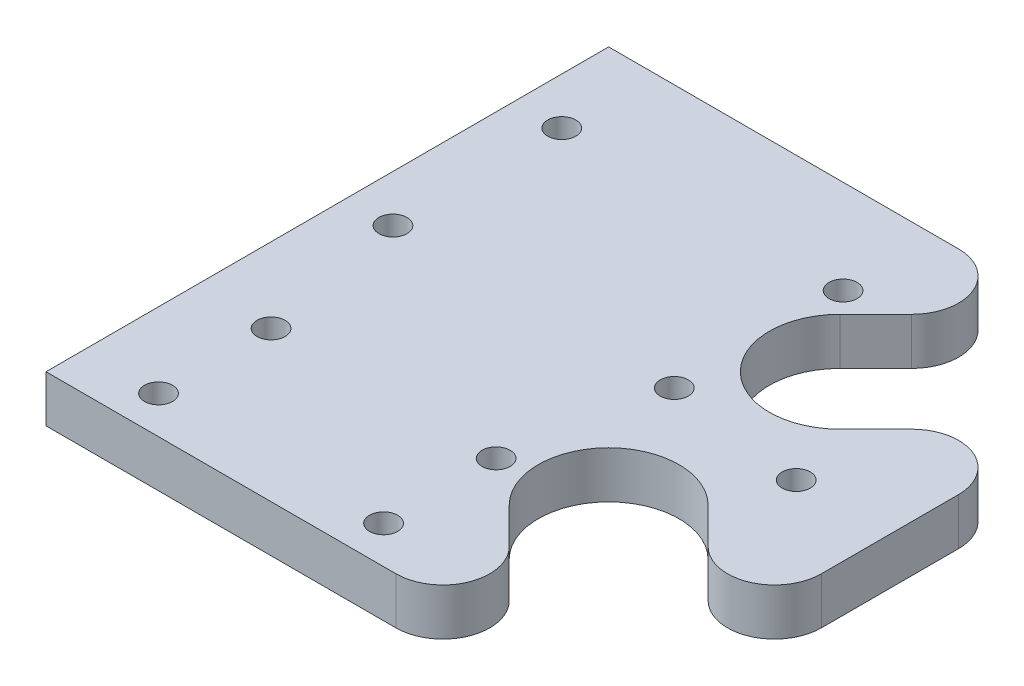
SolidWorks part; units mm, degrees
material "Thornel Mat VMA"
ref_plane "前视基准面" through (0, 0, 0) normal (0, 0, 1) x (1, 0, 0)
ref_plane "上视基准面" through (0, 0, 0) normal (0, 1, 0) x (1, 0, 0)
ref_plane "右视基准面" through (0, 0, 0) normal (1, 0, 0) x (0, 0, -1)
sketch "草图1" plane through (0, 0, 0) normal (0, 1, 0) x (1, 0, 0)
  line L1 (-30, -30) -> (30, -30)
  line L2 (-30, -30) -> (-30, 30)
  line L3 (-30, 30) -> (30, 30)
  line L4 (30, -30) -> (30, 30)
  line L5 (-30, -30) -> (30, 30) construction
  line L6 (-30, 30) -> (30, -30) construction
  point P0 (0, 0)
  dimension "D1" = 60
  dimension "D2" = 60
extrude "凸台-拉伸1" add sketch "草图1" along normal blind 5
sketch "草图2" plane through (0, 5, 0) normal (0, 1, 0) x (1, 0, 0)
  line L0 (-30, 0) -> (30, 0) construction
  line L1 (-30, 30) -> (-30, -30) construction
  line L2 (30, -30) -> (30, 30) construction
  line L3 (30, 30) -> (0, 0) construction
  line L4 (19.3934, 30) -> (7.019, 17.6256)
  line L5 (30, 30) -> (-30, 30) construction
  line L6 (30, 19.3934) -> (17.6256, 7.019)
  line L7 (19.3934, 30) -> (30, 30)
  line L8 (30, 30) -> (30, 19.3934)
  line L9 (19.3934, -30) -> (30, -30)
  line L10 (19.3934, -30) -> (7.019, -17.6256)
  line L11 (30, -19.3934) -> (17.6256, -7.019)
  line L12 (30, -30) -> (30, -19.3934)
  arc A2 (7.019, 17.6256) -> (17.6256, 7.019) centre (12.3223, 12.3223) ccw
  arc A3 (7.019, -17.6256) -> (17.6256, -7.019) centre (12.3223, -12.3223) cw
  dimension "D1" = 15
  dimension "D2" = 25
  dimension "D3" = 45
  dimension "D4" = 30
extrude "切除-拉伸1" cut sketch "草图2" against normal through all
fillet "圆角1" radius 5 4 edges at (19.3934, 2.5, 30) (30, 2.5, 19.3934) (30, 2.5, -19.3934) (19.3934, 2.5, -30)
sketch "草图3" plane through (0, 5, 0) normal (0, 1, 0) x (1, 0, 0)
  line L0 (-30, 24) -> (13.3934, 24) construction
  line L1 (-30, 30) -> (-30, -30) construction
  line L2 (10.8579, 21.4645) -> (7.019, 17.6256) construction
  line L3 (7.3223, 30) -> (-30, 30) construction
  line L5 (-10, 30) -> (-10, -30) construction
  line L6 (-30, -30) -> (7.3223, -30) construction
  line L7 (-30, 20) -> (9.3934, 20) construction
  line L8 (-30, 0) -> (47.4052, 0) construction
  line L9 (30, -7.3223) -> (30, 7.3223) construction
  line L10 (-10, -20) -> (-30, -20) construction
  line L11 (-22, -26) -> (2, -26) construction
  line L12 (-22, -26) -> (-22, -14) construction
  line L13 (-22, -14) -> (2, -14) construction
  line L14 (2, -26) -> (2, -14) construction
  line L15 (-22, -26) -> (2, -14) construction
  line L16 (-22, -14) -> (2, -26) construction
  line L21 (5, 2) -> (-25, 2) construction
  line L22 (5, 2) -> (5, 20) construction
  line L23 (5, 20) -> (-25, 20) construction
  line L24 (-25, 2) -> (-25, 20) construction
  line L25 (5, 2) -> (-25, 20) construction
  line L26 (5, 20) -> (-25, 2) construction
  circle A4 centre (20, 0) radius 1.5
  circle A5 centre (-22, -14) radius 1.5
  circle A6 centre (2, -14) radius 1.5
  circle A7 centre (2, -26) radius 1.5
  circle A8 centre (-22, -26) radius 1.5
  circle A9 centre (-25, 20) radius 1.5
  circle A10 centre (5, 20) radius 1.5
  circle A11 centre (-25, 2) radius 1.5
  circle A12 centre (5, 2) radius 1.5
  point P12 (-10, 11)
  point P30 (-10, -20)
  dimension "D2" = 3
  dimension "D4" = 20
  dimension "D5" = 18
  dimension "D7" = 3
  dimension "D8" = 3
  dimension "D9" = 10
  dimension "D10" = 3
  dimension "D14" = 3
  dimension "D3" = 5
  dimension "D1" = 6
  dimension "D6" = 10
  dimension "D11" = 10
  dimension "D12" = 12
  dimension "D13" = 24
extrude "切除-拉伸2" cut sketch "草图3" against normal through all
